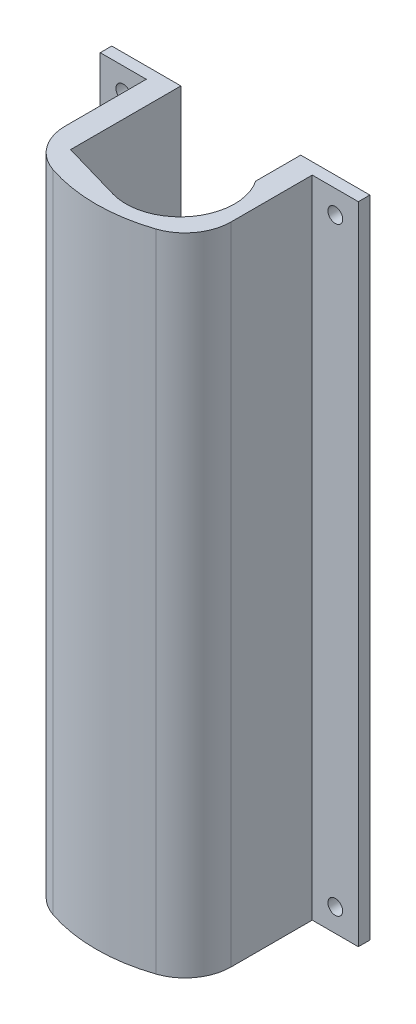
SolidWorks part; units mm, degrees
ref_plane "Front Plane" through (0, 0, 0) normal (0, 0, 1) x (1, 0, 0)
ref_plane "Top Plane" through (0, 0, 0) normal (0, 1, 0) x (1, 0, 0)
ref_plane "Right Plane" through (0, 0, 0) normal (1, 0, 0) x (0, 0, -1)
sketch "Sketch1" plane through (0, 0, 0) normal (0, 1, 0) x (1, 0, 0)
  line L0 (-20.574, -9.6521) -> (-4.162, -14.3967)
  line L1 (-4.1621, 14.3967) -> (-20.574, 9.652) construction
  line L2 (-20.574, 9.652) -> (-20.574, -9.6521)
  line L3 (-39.624, 20.7467) -> (-20.574, 20.7467)
  line L4 (-39.624, 20.7467) -> (-39.624, 17.5717)
  line L6 (12.446, 20.7467) -> (31.496, 20.7467)
  line L7 (-39.624, 17.5717) -> (-26.924, 17.5717)
  line L9 (-26.924, 17.5717) -> (-26.924, -12.8271)
  line L10 (31.496, 20.7467) -> (31.496, 17.5717)
  line L11 (31.496, 17.5717) -> (18.796, 17.5717)
  line L12 (18.796, 17.5717) -> (18.796, -12.8271)
  line L13 (-20.574, 9.652) -> (-20.574, 20.7467)
  line L14 (12.446, 20.7467) -> (12.446, 8.3478)
  arc A0 (-4.162, -14.3967) -> (12.446, 8.3478) centre (0, 0) ccw
  arc A1 (-26.924, -12.8271) -> (18.796, -12.8271) centre (-4.064, 25.294) ccw
  arc A2 (12.446, 8.3478) -> (-4.1621, 14.3967) centre (0, 0) ccw construction
  point P6 (12.446, 14.5473)
  point P16 (21.971, 20.7467)
  dimension "D2" = 14.9863
  dimension "D14" = 6.35
  dimension "D10" = 44.45
  dimension "D1" = 19.3041
  dimension "D3" = 16.4119
  dimension "D4" = 106.124
  dimension "D5" = 20.574
  dimension "D6" = 106.125
  dimension "D7" = 6.35
  dimension "D8" = 6.35
  dimension "D9" = 3.175
  dimension "D11" = 12.7
  dimension "D12" = 3.175
  dimension "D13" = 33.02
extrude "Boss-Extrude1" add sketch "Sketch1" along normal blind 177.8
sketch "Sketch2" plane through (0, 0, -17.5717) normal (0, 0, 1) x (1, 0, 0)
  line L0 (-39.624, 0) -> (-26.924, 0) construction
  line L1 (-39.624, 177.8) -> (-39.624, 0) construction
  line L2 (-39.624, 177.8) -> (-26.924, 177.8) construction
  line L3 (31.496, 177.8) -> (31.496, 0) construction
  circle A0 centre (-33.274, 171.45) radius 2.032
  circle A1 centre (-33.274, 6.35) radius 2.032
  circle A2 centre (25.146, 171.45) radius 2.032
  circle A3 centre (25.146, 6.35) radius 2.032
  dimension "D5" = 4.064
  dimension "D1" = 6.35
  dimension "D2" = 6.35
  dimension "D3" = 6.35
  dimension "D4" = 6.35
extrude "Cut-Extrude1" cut sketch "Sketch2" against normal through all
fillet "Fillet2" radius 12.7 2 edges at (18.796, 88.9, 12.8271) (-26.924, 88.9, 12.8271)
